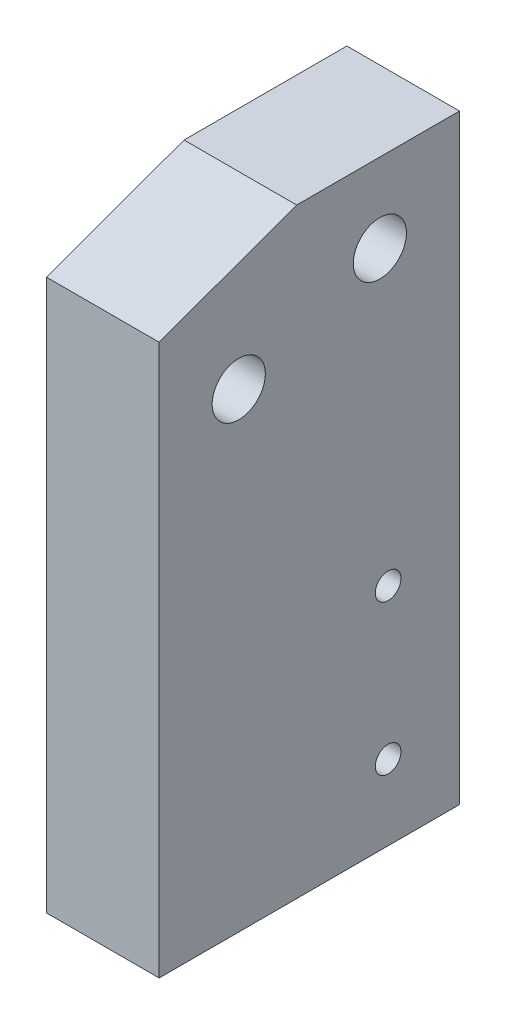
SolidWorks part; units mm, degrees
material "1060 Alloy"
ref_plane "Front Plane" through (0, 0, 0) normal (0, 0, 1) x (1, 0, 0)
ref_plane "Top Plane" through (0, 0, 0) normal (0, 1, 0) x (1, 0, 0)
ref_plane "Right Plane" through (0, 0, 0) normal (1, 0, 0) x (0, 0, -1)
sketch "Sketch1" plane through (0, 0, 0) normal (0, 1, 0) x (1, 0, 0)
  line L1 (0, 0) -> (28.575, 0)
  line L2 (0, 0) -> (0, 76.2)
  line L3 (0, 76.2) -> (28.575, 76.2)
  line L4 (28.575, 0) -> (28.575, 76.2)
  dimension "D1" = 28.575
  dimension "D2" = 76.2
extrude "Boss-Extrude1" add sketch "Sketch1" along normal blind 152.4
sketch "Sketch2" plane through (28.575, 0, 0) normal (1, 0, 0) x (0, 0, -1)
  line L0 (76.2, 139.7) -> (0, 111.9655) construction
  line L3 (76.2, 152.4) -> (76.2, 0) construction
  line L4 (0, 152.4) -> (76.2, 152.4) construction
  line L5 (0, 152.4) -> (0, 0) construction
  dimension "D2" = 20
hole_wizard "1/2 Clearance Hole1" positions "3DSketch2" profile "Sketch4" hole size "1/2" standard "ANSI Inch"
sketch3d "3DSketch2"
  line L0 (28.575, 139.7, -76.2) -> (28.575, 111.9655, 0) construction
  point P0 (28.575, 125.8327, -38.1)
  point P4 (28.575, 132.3482, -56.0011)
  point P6 (28.575, 119.3173, -20.1989)
  point P8 (28.575, 125.8327, -38.1)
  dimension "D1" = 19.05
  dimension "D2" = 19.05
sketch "Sketch4" plane through (28.575, 119.3173, -20.1989) normal (0, 1, 0) x (0, 0, -1)
  line L0 (0, 0) -> (0, 28.575)
  line L1 (0, 28.575) -> (6.7462, 28.575)
  line L2 (6.7462, 28.575) -> (6.7462, 0)
  line L5 (6.7462, 0) -> (0, 0)
  line L11 (0, -6.35) -> (0, 107.95) construction
  dimension "Thru Hole Dia." = 13.4925
  dimension "Thru Hole Depth" = 28.575
sketch "Sketch5" plane through (28.575, 0, 0) normal (1, 0, 0) x (0, 0, -1)
  line L0 (38.1, 125.8327) -> (12.5419, 196.053) construction
  line L1 (28.4303, 152.4) -> (38.1, 125.8327)
  line L2 (76.2, 139.7) -> (0, 111.9655) construction
  line L3 (38.1, 125.8327) -> (12.5419, 125.8327) construction
  line L4 (12.5419, 125.8327) -> (12.5419, 196.053) construction
  line L5 (0, 152.4) -> (76.2, 152.4) construction
  line L6 (12.5419, 125.8327) -> (12.5419, 116.5304) construction
  line L7 (12.5419, 116.5304) -> (38.1, 125.8327)
  dimension "D1" = 74.7268
ref_plane "Plane1" through (0, 98.868, 35.985) normal (0, 0.9397, 0.342) x (0, -0.342, 0.9397)
hole_wizard "Tap Drill for 5/16-18 Tap1" positions "Sketch7" profile "Sketch8" hole size "5/16-18" standard "ANSI Inch"
sketch "Sketch7" plane through (28.575, 0, 0) normal (1, 0, 0) x (0, 0, -1)
  point P0 (58.1, 57.15)
  point P2 (58.1, 19.05)
sketch "Sketch8" plane through (28.575, 57.15, -58.1) normal (0, 1, 0) x (0, 0, -1)
  line L0 (0, 0) -> (0, 14.6611)
  line L1 (0, 14.6611) -> (3.2639, 12.7)
  line L2 (3.2639, 12.7) -> (3.2639, 0)
  line L5 (3.2639, 0) -> (0, 0)
  line L10 (0, 14.6611) -> (-3.2639, 12.7) construction
  line L11 (0, -6.35) -> (0, 107.95) construction
  dimension "Hole Dia." = 6.5278
  dimension "Hole Depth" = 12.7
  dimension "Drill Angle" = 118
hole_wizard "Tap Drill for 5/16-18 Tap2" positions "Sketch9" profile "Sketch10" hole size "5/16-18" standard "ANSI Inch"
sketch "Sketch9" plane through (0, 0, 0) normal (-1, 0, 0) x (0, 0, 1)
  point P0 (-18.1, 57.15)
  point P2 (-18.1, 19.05)
sketch "Sketch10" plane through (0, 57.15, -18.1) normal (0, 1, 0) x (0, 0, 1)
  line L0 (0, 0) -> (0, 14.6611)
  line L1 (0, 14.6611) -> (3.2639, 12.7)
  line L2 (3.2639, 12.7) -> (3.2639, 0)
  line L5 (3.2639, 0) -> (0, 0)
  line L10 (0, 14.6611) -> (-3.2639, 12.7) construction
  line L11 (0, -6.35) -> (0, 107.95) construction
  dimension "Hole Dia." = 6.5278
  dimension "Hole Depth" = 12.7
  dimension "Drill Angle" = 118
sketch "Sketch12" plane through (0, 0, 0) normal (-1, 0, 0) x (0, 0, 1)
  line L0 (-34.893, 152.4) -> (0, 139.7)
  line L1 (-76.2, 152.4) -> (0, 152.4) construction
  line L2 (0, 152.4) -> (0, 0) construction
  line L3 (0, 139.7) -> (0, 152.4)
  line L4 (0, 152.4) -> (-34.893, 152.4)
  line L5 (99.9317, 75.5933) -> (-27.9617, 122.1427) construction
  dimension "D1" = 0
  dimension "D2" = 12.7
extrude "Cut-Extrude1" cut sketch "Sketch12" against normal through all
equation "\"wheel angle\"= 20"
equation "\"hole offset\"= 0.5"
equation "\"D1@Sketch2\"=\"hole offset\""
equation "\"D2@Sketch2\"=\"wheel angle\""
equation "\"hole spacing\"= 0.75"
equation "\"length\"= 8 - 2"
equation "\"D1@Boss-Extrude1\"=\"length\""
